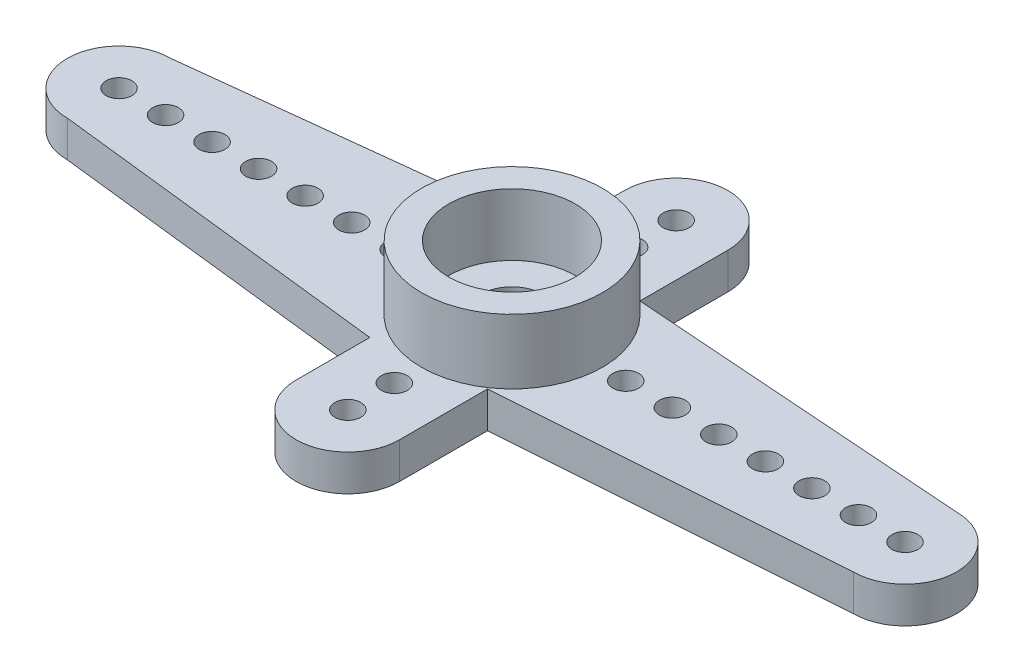
SolidWorks part; units mm, degrees
other "Camera1"
material "ABS"
ref_plane "Front Plane" through (0, 0, 0) normal (0, 0, 1) x (1, 0, 0)
ref_plane "Top Plane" through (0, 0, 0) normal (0, 1, 0) x (1, 0, 0)
ref_plane "Right Plane" through (0, 0, 0) normal (1, 0, 0) x (0, 0, -1)
sketch "Sketch1" plane through (0, 0, 0) normal (0, 1, 0) x (1, 0, 0)
  line L0 (-17.2, 0) -> (17.2, 0) construction
  line L1 (0, -8.35) -> (0, 8.35) construction
  line L2 (-15.2, 2) -> (-2, 2.95)
  line L3 (-15.2, -2) -> (-2, -2.95)
  line L4 (2, 6.35) -> (2, 3.5)
  line L5 (-2, 6.35) -> (-2, 2.95)
  line L6 (2, -6.35) -> (2, -3.5)
  line L7 (-2, -6.35) -> (-2, -2.95)
  line L8 (15.2, 2) -> (2, 3.5)
  line L9 (15.2, -2) -> (2, -3.5)
  circle A0 centre (0, 0) radius 3.5 construction
  arc A1 (-15.2, 2) -> (-15.2, -2) centre (-15.2, 0) ccw
  arc A2 (15.2, 2) -> (15.2, -2) centre (15.2, 0) cw
  arc A3 (2, 6.35) -> (-2, 6.35) centre (0, 6.35) ccw
  circle A4 centre (0, 6.35) radius 0.5
  circle A5 centre (0, 4.55) radius 0.5
  circle A6 centre (0, -4.55) radius 0.5
  circle A7 centre (0, -6.35) radius 0.5
  arc A8 (2, -6.35) -> (-2, -6.35) centre (0, -6.35) cw
  circle A10 centre (-15.2, 0) radius 0.5
  circle A11 centre (15.2, 0) radius 0.5
  circle A12 centre (-13.4, 0) radius 0.5
  circle A13 centre (-11.6, 0) radius 0.5
  circle A14 centre (-9.8, 0) radius 0.5
  circle A15 centre (-8, 0) radius 0.5
  circle A16 centre (-6.2, 0) radius 0.5
  circle A17 centre (-4.4, 0) radius 0.5
  circle A18 centre (13.4, 0) radius 0.5
  circle A19 centre (11.6, 0) radius 0.5
  circle A20 centre (9.8, 0) radius 0.5
  circle A21 centre (8, 0) radius 0.5
  circle A22 centre (6.2, 0) radius 0.5
  circle A23 centre (4.4, 0) radius 0.5
  point P5 (0, 0)
  point P8 (0, 0)
  point P25 (0, 6.85)
  point P26 (0, 4.05)
  dimension "D1" = 7
  dimension "D4" = 4
  dimension "D6" = 1
  dimension "D2" = 34.4
  dimension "D3" = 16.7
  dimension "D5" = 2
  dimension "D7" = 2.8
  dimension "D8" = 7
  dimension "D10" = 5.9
  dimension "D11" = 7
  dimension "D12" = 7
extrude "Boss-Extrude1" add sketch "Sketch1" along normal blind 1.4
sketch "Sketch2" plane through (0, 0, 0) normal (0, -1, 0) x (1, 0, 0)
  circle A0 centre (0, 0) radius 2.35
  dimension "D1" = 4.7
extrude "Cut-Extrude1" cut sketch "Sketch2" against normal blind 1
sketch "Sketch3" plane through (0, 1.4, 0) normal (0, 1, 0) x (1, 0, 0)
  circle A0 centre (0, 0) radius 2.45
  circle A1 centre (0, 0) radius 3.5
  dimension "D1" = 4.9
  dimension "D2" = 7
extrude "Boss-Extrude2" add sketch "Sketch3" along normal blind 2.5
sketch "Sketch4" plane through (0, 1.4, 0) normal (0, 1, 0) x (1, 0, 0)
  circle A0 centre (0, 0) radius 1.2
  dimension "D1" = 2.4
extrude "Cut-Extrude2" cut sketch "Sketch4" against normal through all
sketch "Sketch5" plane through (0, 1.4, 0) normal (0, 1, 0) x (1, 0, 0)
  circle A0 centre (0, 0) radius 1.2 construction
  circle A1 centre (0, 0) radius 2.45
  circle A2 centre (0, 0) radius 2.45
  circle A3 centre (0, 0) radius 1.2
  dimension "D1" = 0
extrude "Boss-Extrude3" add sketch "Sketch5" along normal blind 0.1
sketch "Sketch6" plane through (0, 0, 0) normal (0, -1, 0) x (1, 0, 0)
  line L0 (-2, -2.95) -> (-15.2, -2) construction
  line L1 (-1.8686, -2.9595) -> (-15.2, -2)
  line L2 (-15.2, 2) -> (-2, 2.95) construction
  line L3 (-15.2, 2) -> (-1.8686, 2.9595)
  line L4 (0, -9.3016) -> (0, 8.6978) construction
  line L5 (1.8686, -2.9595) -> (15.2, -2)
  line L6 (15.2, 2) -> (1.8686, 2.9595)
  line L8 (-17.8676, -8.836) -> (17.8676, -8.836)
  line L9 (-17.8676, -8.836) -> (-17.8676, 8.836)
  line L10 (-17.8676, 8.836) -> (17.8676, 8.836)
  line L11 (17.8676, -8.836) -> (17.8676, 8.836)
  line L12 (-17.8676, -8.836) -> (17.8676, 8.836) construction
  line L13 (-17.8676, 8.836) -> (17.8676, -8.836) construction
  arc A0 (-15.2, 2) -> (-15.2, -2) centre (-15.2, 0) ccw construction
  arc A1 (-15.2, 2) -> (-15.2, -2) centre (-15.2, 0) ccw
  circle A2 centre (0, 0) radius 3.5 construction
  arc A3 (1.8686, 2.9595) -> (-1.8686, 2.9595) centre (0, 0) ccw
  arc A4 (15.2, 2) -> (15.2, -2) centre (15.2, 0) cw
  arc A5 (-1.8686, -2.9595) -> (1.8686, -2.9595) centre (0, 0) ccw
extrude "Cut-Extrude4" cut sketch "Sketch6" against normal through all
sketch "Sketch7" plane through (0, 0, 0) normal (0, -1, 0) x (1, 0, 0)
  line L0 (0, 3.5) -> (-17.7318, 3.5)
  line L1 (-17.7318, 3.5) -> (-17.7318, -3.5)
  line L2 (-17.7318, -3.5) -> (0, -3.5)
  circle A0 centre (0, 0) radius 3.5 construction
  arc A1 (0, 3.5) -> (0, -3.5) centre (0, 0) ccw
extrude "Cut-Extrude5" cut sketch "Sketch7" against normal through all
pattern_circular "CirPattern2" count 2 over 360 about axis through (0, 0, 0) along (0, 1, 0) of "Boss-Extrude1"
sketch "Sketch9" plane through (0, 1.4, 0) normal (0, 1, 0) x (1, 0, 0)
  circle A0 centre (0, 0) radius 2.45 construction
  circle A1 centre (0, 0) radius 1.2 construction
  circle A2 centre (0, 0) radius 2.45
  circle A3 centre (0, 0) radius 1.2
  point P6 (0, 0)
extrude "Cut-Extrude6" cut sketch "Sketch9" against normal through all from surface at 0 contours A3 starting at face at (0, 1.4, 0)
